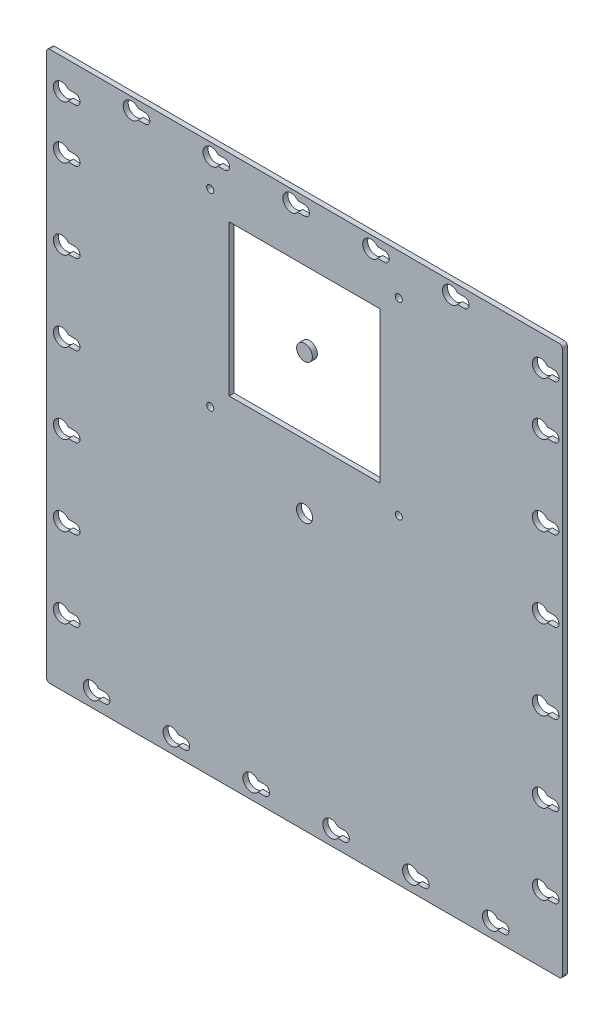
SolidWorks part; units mm, degrees
material "6061 Alloy"
ref_plane "Front Plane" through (0, 0, 0) normal (0, 0, 1) x (1, 0, 0)
ref_plane "Top Plane" through (0, 0, 0) normal (0, 1, 0) x (1, 0, 0)
ref_plane "Right Plane" through (0, 0, 0) normal (1, 0, 0) x (0, 0, -1)
sketch "Sketch1" plane through (0, 0, 0) normal (0, 0, 1) x (1, 0, 0)
  line L0 (0, 0) -> (0, -174.745)
  line L3 (0, -174.745) -> (165.1, -174.745)
  line L5 (0, 0) -> (165.1, 0)
  line L6 (165.1, -174.745) -> (165.1, 0)
  line L7 (82.55, 0) -> (82.55, -174.745) construction
  line L8 (31.75, -2.2625) -> (29.6344, -2.2625)
  line L9 (31.75, -5.4375) -> (29.6344, -5.4375)
  line L10 (9.525, -24.9325) -> (7.4094, -24.9325)
  line L11 (9.525, -28.1075) -> (7.4094, -28.1075)
  line L12 (161.925, -24.9325) -> (159.8094, -24.9325)
  line L13 (161.925, -28.1075) -> (159.8094, -28.1075)
  line L14 (57.15, -2.2625) -> (55.0344, -2.2625)
  line L15 (57.15, -5.4375) -> (55.0344, -5.4375)
  line L16 (82.55, -2.2625) -> (80.4344, -2.2625)
  line L17 (82.55, -5.4375) -> (80.4344, -5.4375)
  line L18 (107.95, -2.2625) -> (105.8344, -2.2625)
  line L19 (107.95, -5.4375) -> (105.8344, -5.4375)
  line L20 (133.35, -2.2625) -> (131.2344, -2.2625)
  line L21 (133.35, -5.4375) -> (131.2344, -5.4375)
  line L22 (9.525, -50.3325) -> (7.4094, -50.3325)
  line L23 (9.525, -53.5075) -> (7.4094, -53.5075)
  line L24 (161.925, -50.3325) -> (159.8094, -50.3325)
  line L25 (161.925, -53.5075) -> (159.8094, -53.5075)
  line L26 (9.525, -75.7325) -> (7.4094, -75.7325)
  line L27 (9.525, -78.9075) -> (7.4094, -78.9075)
  line L28 (161.925, -75.7325) -> (159.8094, -75.7325)
  line L29 (161.925, -78.9075) -> (159.8094, -78.9075)
  line L30 (9.525, -101.1325) -> (7.4094, -101.1325)
  line L31 (9.525, -104.3075) -> (7.4094, -104.3075)
  line L32 (161.925, -101.1325) -> (159.8094, -101.1325)
  line L33 (161.925, -104.3075) -> (159.8094, -104.3075)
  line L34 (9.525, -126.5325) -> (7.4094, -126.5325)
  line L35 (9.525, -129.7075) -> (7.4094, -129.7075)
  line L36 (161.925, -126.5325) -> (159.8094, -126.5325)
  line L37 (161.925, -129.7075) -> (159.8094, -129.7075)
  line L38 (9.525, -151.9325) -> (7.4094, -151.9325)
  line L39 (9.525, -155.1075) -> (7.4094, -155.1075)
  line L40 (161.925, -151.9325) -> (159.8094, -151.9325)
  line L41 (161.925, -155.1075) -> (159.8094, -155.1075)
  line L42 (19.05, -168.395) -> (16.9344, -168.395)
  line L43 (19.05, -171.57) -> (16.9344, -171.57)
  line L44 (44.45, -168.395) -> (42.3344, -168.395)
  line L45 (44.45, -171.57) -> (42.3344, -171.57)
  line L46 (69.85, -168.395) -> (67.7344, -168.395)
  line L47 (69.85, -171.57) -> (67.7344, -171.57)
  line L48 (95.25, -168.395) -> (93.1344, -168.395)
  line L49 (95.25, -171.57) -> (93.1344, -171.57)
  line L50 (120.65, -168.395) -> (118.5344, -168.395)
  line L51 (120.65, -171.57) -> (118.5344, -171.57)
  line L52 (146.05, -168.395) -> (143.9344, -168.395)
  line L53 (146.05, -171.57) -> (143.9344, -171.57)
  line L54 (0.5, 0) -> (0.5, -174.745)
  line L55 (164.6, -174.745) -> (164.6, 0)
  line L56 (0.5, -174.745) -> (164.6, -174.745)
  line L57 (9.525, -8.1) -> (7.4094, -8.1)
  line L58 (9.525, -11.275) -> (7.4094, -11.275)
  line L59 (161.925, -8.1) -> (159.8094, -8.1)
  line L60 (161.925, -11.275) -> (159.8094, -11.275)
  circle A41 centre (9.525, -153.52) radius 1.5875
  circle A42 centre (19.05, -169.9825) radius 1.5875
  circle A43 centre (9.525, -128.12) radius 1.5875
  circle A44 centre (9.525, -102.72) radius 1.5875
  circle A45 centre (9.525, -77.32) radius 1.5875
  circle A46 centre (9.525, -51.92) radius 1.5875
  circle A47 centre (9.525, -26.52) radius 1.5875
  circle A49 centre (44.45, -169.9825) radius 1.5875
  circle A50 centre (69.85, -169.9825) radius 1.5875
  circle A51 centre (95.25, -169.9825) radius 1.5875
  circle A52 centre (120.65, -169.9825) radius 1.5875
  circle A68 centre (146.05, -169.9825) radius 1.5875
  circle A69 centre (107.95, -3.85) radius 1.5875
  circle A70 centre (82.55, -3.85) radius 1.5875
  circle A71 centre (57.15, -3.85) radius 1.5875
  circle A72 centre (9.525, -1.12) radius 1.5875 [skipped]
  circle A73 centre (133.35, -3.85) radius 1.5875
  circle A74 centre (31.75, -3.85) radius 1.5875
  circle A75 centre (161.925, -26.52) radius 1.5875
  circle A76 centre (161.925, -51.92) radius 1.5875
  circle A77 centre (161.925, -77.32) radius 1.5875
  circle A78 centre (161.925, -102.72) radius 1.5875
  circle A79 centre (161.925, -128.12) radius 1.5875
  circle A80 centre (161.925, -153.52) radius 1.5875
  circle A81 centre (27.5125, -3.85) radius 2.65
  circle A83 centre (5.2875, -26.52) radius 2.65
  circle A84 centre (157.6875, -26.52) radius 2.65
  circle A85 centre (52.9125, -3.85) radius 2.65
  circle A86 centre (78.3125, -3.85) radius 2.65
  circle A87 centre (103.7125, -3.85) radius 2.65
  circle A88 centre (129.1125, -3.85) radius 2.65
  circle A89 centre (5.2875, -51.92) radius 2.65
  circle A90 centre (157.6875, -51.92) radius 2.65
  circle A91 centre (5.2875, -77.32) radius 2.65
  circle A92 centre (157.6875, -77.32) radius 2.65
  circle A93 centre (5.2875, -102.72) radius 2.65
  circle A94 centre (157.6875, -102.72) radius 2.65
  circle A95 centre (5.2875, -128.12) radius 2.65
  circle A96 centre (157.6875, -128.12) radius 2.65
  circle A97 centre (5.2875, -153.52) radius 2.65
  circle A98 centre (157.6875, -153.52) radius 2.65
  circle A99 centre (14.8125, -169.9825) radius 2.65
  circle A100 centre (40.2125, -169.9825) radius 2.65
  circle A101 centre (65.6125, -169.9825) radius 2.65
  circle A102 centre (91.0125, -169.9825) radius 2.65
  circle A103 centre (116.4125, -169.9825) radius 2.65
  circle A104 centre (141.8125, -169.9825) radius 2.65
  circle A105 centre (82.55, -87.3725) radius 2.5527
  circle A107 centre (9.525, -9.6875) radius 1.5875
  circle A108 centre (5.2875, -9.6875) radius 2.65
  circle A109 centre (161.925, -9.6875) radius 1.5875
  circle A110 centre (157.6875, -9.6875) radius 2.65
  dimension "D3" = 3.175
  dimension "D8" = 3.175
  dimension "D21" = 5.3
  dimension "D31" = 5.1054
  dimension "D33" = 5.3
  dimension "D1" = 165.1
  dimension "D2" = 174.745
  dimension "D5" = 9.525
  dimension "D4" = 21.225
  dimension "D6" = 19.05
  dimension "D7" = 4.7625
  dimension "D9" = 25.4
  dimension "D10" = 25.4
  dimension "D15" = 25.4
  dimension "D12" = 3.85
  dimension "D13" = 31.75
  dimension "D17" = 31.75
  dimension "D18" = 3.175
  dimension "D20" = 25.4
  dimension "D23" = 25.4
  dimension "D25" = 25.4
  dimension "D27" = 25.4
  dimension "D28" = 0.5
  dimension "D29" = 0.5
  dimension "D30" = 87.3725
  dimension "D34" = 16.8325
  dimension "D35" = 5.8375
  dimension "D11" = 7
  dimension "D14" = 5
  dimension "D16" = 5
  dimension "D19" = 6
  dimension "D22" = 5
  dimension "D24" = 6
  dimension "D26" = 6
extrude "Boss-Extrude1" add sketch "Sketch1" along normal blind 1.5875 contours L7 L5 L0 L3 A50 A41 A42 A43 A44 A45 A46 A47 A73 A49 | L5 L7 A70 A105 L56 L55 A84 L12 A75 L13 A87 L18 A69 L19 A88 L20 A73 L21 A90 L24 A76 L25 A92 L28 A77 L29 A94 L32 A78 L33 A96 L36 A79 L37 A98 L40 A80 L41 A102 L48
fillet "Fillet1" radius 1 4 edges at (164.6, 0, 0.7937) (164.6, -174.745, 0.7937) (0.5, -174.745, 0.7937) (0.5, 0, 0.7937)
sketch "Sketch2" plane through (0, 0, 1.5875) normal (0, 0, 1) x (1, 0, 0)
  line L0 (1.5, 0) -> (163.6, 0) construction
  line L1 (58.55, -18.9884) -> (106.55, -18.9884)
  line L2 (58.55, -18.9884) -> (58.55, -66.9884)
  line L3 (58.55, -66.9884) -> (106.55, -66.9884)
  line L4 (106.55, -18.9884) -> (106.55, -66.9884)
  line L6 (52.55, -12.9884) -> (112.55, -12.9884) construction
  line L7 (52.55, -12.9884) -> (52.55, -72.9884) construction
  line L8 (52.55, -72.9884) -> (112.55, -72.9884) construction
  line L9 (112.55, -12.9884) -> (112.55, -72.9884) construction
  line L10 (82.55, -72.9884) -> (82.55, -12.9884) construction
  line L11 (52.55, -42.9884) -> (112.55, -42.9884) construction
  circle A0 centre (82.55, -42.9884) radius 2.5
  circle A1 centre (52.55, -12.9884) radius 1.13
  circle A2 centre (112.55, -72.9884) radius 1.13
  circle A3 centre (112.55, -12.9884) radius 1.13
  circle A4 centre (52.55, -72.9884) radius 1.13
  point P6 (82.55, 0)
  point P7 (82.55, -18.9884)
  point P11 (106.55, -42.9884)
  dimension "D4" = 5
  dimension "D2" = 2.26
  dimension "D1" = 48
  dimension "D3" = 18.9884
  dimension "D5" = 60
extrude "Cut-Extrude1" cut sketch "Sketch2" against normal blind 10 contours L4 L1 L2 L3 A0 | A3 | A2 | A4 | A1
equation "\"D8@Sketch1\"=\"D3@Sketch1\""
equation "\"D29@Sketch1\"=\"D28@Sketch1\""
equation "\"D30@Sketch1\"=\"D2@Sketch1\"/2"
